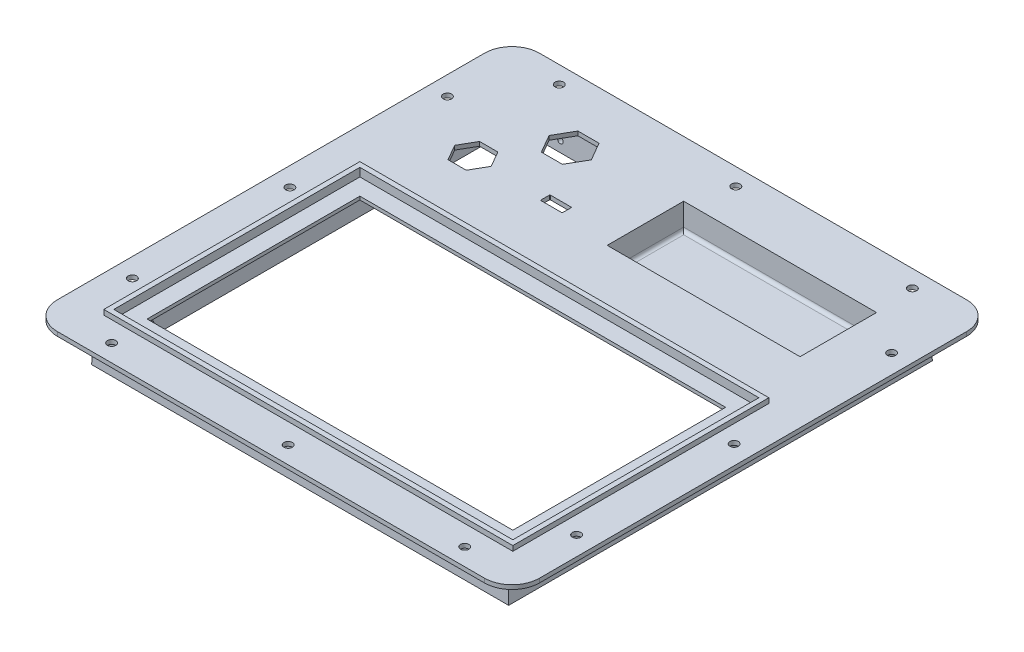
SolidWorks part; units mm, degrees
material "Alumina"
ref_plane "Front Plane" through (0, 0, 0) normal (0, 0, 1) x (1, 0, 0)
ref_plane "Top Plane" through (0, 0, 0) normal (0, 1, 0) x (1, 0, 0)
ref_plane "Right Plane" through (0, 0, 0) normal (1, 0, 0) x (0, 0, -1)
sketch "Sketch1" plane through (0, 0, 0) normal (0, 1, 0) x (1, 0, 0)
  line L1 (-123, -77) -> (123, -77)
  line L2 (-123, -77) -> (-123, 77)
  line L3 (-123, 77) -> (123, 77)
  line L4 (123, -77) -> (123, 77)
  line L5 (-123, -77) -> (123, 77) construction
  line L6 (-123, 77) -> (123, -77) construction
  point P0 (0, 0)
  dimension "D1" = 246
  dimension "D2" = 154
extrude "Boss-Extrude1" add sketch "Sketch1" against normal blind 7
sketch "Sketch2" plane through (0, 0, 0) normal (0, 1, 0) x (1, 0, 0)
  line L1 (-120, -74) -> (120, -74)
  line L2 (-120, -74) -> (-120, 74)
  line L3 (-120, 74) -> (120, 74)
  line L4 (120, -74) -> (120, 74)
  line L5 (-120, -74) -> (120, 74) construction
  line L6 (-120, 74) -> (120, -74) construction
  point P0 (0, 0)
  dimension "D1" = 240
  dimension "D2" = 148
extrude "Cut-Extrude1" cut sketch "Sketch2" against normal blind 5
sketch "Sketch3" plane through (0, -5, 0) normal (0, 1, 0) x (1, 0, 0)
  line L0 (120, 74) -> (-120, 74) construction
  line L1 (-110, -64) -> (110, -64)
  line L2 (-110, -64) -> (-110, 64)
  line L3 (-110, 64) -> (110, 64)
  line L4 (110, -64) -> (110, 64)
  line L5 (-110, -64) -> (110, 64) construction
  line L6 (-110, 64) -> (110, -64) construction
  line L7 (-120, 74) -> (-120, -74) construction
  point P0 (0, 0)
  dimension "D1" = 10
  dimension "D2" = 10
extrude "Cut-Extrude2" cut sketch "Sketch3" against normal blind 5
sketch "Sketch6" plane through (0, 0, 0) normal (0, 1, 0) x (1, 0, 0)
  line L1 (-128.49, -99.5) -> (128.49, -99.5)
  line L5 (-123, -77) -> (123, -77) construction
  line L8 (-145, -82.99) -> (-145, 173.99)
  line L13 (123, -77) -> (123, 77) construction
  line L14 (-123, 77) -> (-123, -77) construction
  line L16 (145, 173.99) -> (145, -82.99)
  line L17 (123, -77) -> (123, 77)
  line L19 (123, 77) -> (-123, 77) construction
  line L20 (-123, -77) -> (123, -77)
  line L21 (-123, 77) -> (-123, -77)
  line L22 (123, 77) -> (-123, 77)
  line L24 (-128.49, 190.5) -> (128.49, 190.5)
  arc A4 (128.49, 190.5) -> (145, 173.99) centre (128.49, 173.99) cw
  arc A5 (-145, 173.99) -> (-128.49, 190.5) centre (-128.49, 173.99) cw
  arc A6 (-128.49, -99.5) -> (-145, -82.99) centre (-128.49, -82.99) cw
  arc A7 (128.49, -99.5) -> (145, -82.99) centre (128.49, -82.99) ccw
  point P0 (0, 0)
  point P2 (0, -99.5)
  point P4 (-146.3741, 193.3595)
  point P9 (-176.0379, 201.6571)
  dimension "D3" = 22
  dimension "D1" = 16.51
  dimension "D10" = 99.5
  dimension "D9" = 16.51
  dimension "D2" = 22.5
  dimension "D6" = 290
  dimension "D12" = 290
extrude "Boss-Extrude2" add sketch "Sketch6" against normal blind 2.5 from offset 3 offset against normal yes
sketch "Sketch8" plane through (0, -5, 0) normal (0, 1, 0) x (1, 0, 0)
  line L0 (-120, -74) -> (120, -74) construction
  line L1 (-19, -73.1) -> (20, -73.1)
  line L2 (-19, -73.1) -> (-19, -72.8)
  line L3 (-19, -72.8) -> (20, -72.8)
  line L4 (20, -73.1) -> (20, -72.8)
  line L5 (-19, -73.1) -> (20, -72.8) construction
  line L6 (-19, -72.8) -> (20, -73.1) construction
  line L8 (-42.26, -73.1) -> (-30, -73.1)
  line L9 (-42.26, -73.1) -> (-42.26, -72.8)
  line L10 (-42.26, -72.8) -> (-30, -72.8)
  line L11 (-30, -73.1) -> (-30, -72.8)
  line L12 (-42.26, -73.1) -> (-30, -72.8) construction
  line L13 (-42.26, -72.8) -> (-30, -73.1) construction
  point P0 (0.5, -72.95)
  point P7 (-36.13, -72.95)
  dimension "D1" = 19
  dimension "D2" = 20
  dimension "D3" = 0.3
  dimension "D4" = 0.9
  dimension "D5" = 12.26
  dimension "D6" = 30
extrude "Cut-Extrude5" cut sketch "Sketch8" against normal blind 5
sketch "Sketch9" plane through (0, -5, 0) normal (0, 1, 0) x (1, 0, 0)
  line L4 (-120, -74) -> (120, -74) construction
  line L5 (120, -74) -> (120, 74) construction
  circle A0 centre (119, -46.2) radius 0.5
  circle A1 centre (119, -42.7) radius 0.5
  dimension "D1" = 1
  dimension "D2" = 1
  dimension "D3" = 27.8
  dimension "D4" = 31.3
extrude "Cut-Extrude6" cut sketch "Sketch9" against normal blind 5
sketch "Sketch10" plane through (0, -3, 0) normal (0, 1, 0) x (1, 0, 0)
  line L0 (0, 157.1305) -> (0, -54.124) construction
  line L1 (-84.5431, 45.5) -> (100.6663, 45.5) construction
  line L2 (145, -82.99) -> (145, 173.99) construction
  circle A0 centre (-133.604, 140.242) radius 2.54
  circle A1 centre (-106.172, 180.12) radius 2.54
  circle A2 centre (-133.604, -49.242) radius 2.54
  circle A3 centre (-133.604, 45.5) radius 2.54
  circle A4 centre (0, 180.12) radius 2.54
  circle A5 centre (0, -89.12) radius 2.54
  circle A6 centre (-106.172, -89.12) radius 2.54
  circle A7 centre (106.172, -89.12) radius 2.54
  circle A8 centre (133.604, 45.5) radius 2.54
  circle A9 centre (133.604, -49.242) radius 2.54
  circle A10 centre (106.172, 180.12) radius 2.54
  circle A11 centre (133.604, 140.242) radius 2.54
  point P29 (145, 45.5)
  dimension "D3" = 5.08
  dimension "D1" = 94.742
  dimension "D2" = 133.604
  dimension "D4" = 134.62
  dimension "D5" = 106.172
  dimension "D6" = 45.5
extrude "Cut-Extrude7" cut sketch "Sketch10" against normal blind 5
sketch "Sketch11" plane through (0, -5.5, 0) normal (0, -1, 0) x (1, 0, 0)
  line L0 (0, 81.15) -> (0, 99.5) construction
  line L1 (-124.65, -172.15) -> (124.65, -172.15)
  line L2 (-124.65, -172.15) -> (-124.65, 81.15)
  line L3 (-124.65, 81.15) -> (124.65, 81.15)
  line L4 (124.65, -172.15) -> (124.65, 81.15)
  line L5 (-124.65, -172.15) -> (124.65, 81.15) construction
  line L6 (-124.65, 81.15) -> (124.65, -172.15) construction
  line L7 (-128.49, 99.5) -> (128.49, 99.5) construction
  line L8 (0, -172.15) -> (0, -190.5) construction
  line L9 (128.49, -190.5) -> (-128.49, -190.5) construction
  line L10 (-122.65, 79.15) -> (122.65, 79.15)
  line L11 (122.65, -170.15) -> (122.65, 79.15)
  line L12 (-122.65, -170.15) -> (122.65, -170.15)
  line L13 (-122.65, -170.15) -> (-122.65, 79.15)
  point P0 (0, -45.5)
  point P10 (0, -142.2375)
  dimension "D1" = 253.3
  dimension "D2" = 249.3
  dimension "D3" = 2
extrude "Boss-Extrude3" add sketch "Sketch11" along normal blind 22 draft 2 draft outward yes
sketch "Sketch12" plane through (124.3063, 4.3409, 0) normal (0.9994, 0.0349, 0) x (0, 0, -1)
  line L0 (45.5, -31.8603) -> (45.5, 60.7594) construction
  line L1 (172.9183, -31.8603) -> (-81.9183, -31.8603) construction
  circle A0 centre (-49.5, -16.8603) radius 1.7
  circle A1 centre (140.5, -16.8603) radius 1.7
  dimension "D1" = 3.4
  dimension "D2" = 15
  dimension "D3" = 95
extrude "Cut-Extrude8" cut sketch "Sketch12" against normal through all
sketch "Sketch13" plane through (0, 2.8237, 80.8593) normal (0, 0.0349, 0.9994) x (1, 0, 0)
  line L0 (0, 0) -> (0, -78.1597) construction
  line L1 (125.4183, -30.3422) -> (-125.4183, -30.3422) construction
  circle A0 centre (-95, -15.3422) radius 1.7
  circle A1 centre (95, -15.3422) radius 1.7
  dimension "D1" = 3.4
  dimension "D2" = 95
  dimension "D3" = 15
extrude "Cut-Extrude9" cut sketch "Sketch13" against normal through all
sketch "Sketch14" plane through (0, -5.5, 0) normal (0, -1, 0) x (1, 0, 0)
  line L0 (123, -77) -> (-123, -77) construction
  line L1 (-10, -108.75) -> (110, -108.75)
  line L2 (-10, -108.75) -> (-10, -158.75)
  line L3 (-10, -158.75) -> (110, -158.75)
  line L4 (110, -108.75) -> (110, -158.75)
  line L5 (-10, -108.75) -> (110, -158.75) construction
  line L6 (-10, -158.75) -> (110, -108.75) construction
  line L8 (123, 77) -> (123, -77) construction
  point P0 (50, -133.75)
  dimension "D1" = 120
  dimension "D2" = 50
  dimension "D3" = 31.75
  dimension "D4" = 13
extrude "Boss-Extrude4" add sketch "Sketch14" along normal blind 15
sketch "Sketch15" plane through (0, -20.5, 0) normal (0, -1, 0) x (1, 0, 0)
  line L0 (108, -110.75) -> (-8, -110.75)
  line L1 (-8, -110.75) -> (-8, -156.75)
  line L2 (-8, -156.75) -> (108, -156.75)
  line L3 (108, -156.75) -> (108, -110.75)
  line L4 (110, -158.75) -> (110, -108.75)
  line L5 (110, -108.75) -> (-10, -108.75)
  line L6 (-10, -108.75) -> (-10, -158.75)
  line L7 (-10, -158.75) -> (110, -158.75)
  line L8 (110, -158.75) -> (110, -108.75) construction
  line L9 (110, -108.75) -> (-10, -108.75) construction
  line L10 (-10, -108.75) -> (-10, -158.75) construction
  line L11 (-10, -158.75) -> (110, -158.75) construction
  dimension "D1" = 0
  dimension "D2" = 2
extrude "Cut-Extrude10" cut sketch "Sketch15" against normal through all from offset 2 offset against normal yes
fillet "Fillet1" radius 2 4 edges at (50, -18.5, -156.75) (-8, -18.5, -133.75) (50, -18.5, -110.75) (108, -18.5, -133.75)
sketch "Sketch16" plane through (0, -3, 0) normal (0, 1, 0) x (1, 0, 0)
  line L0 (128.49, 190.5) -> (-128.49, 190.5) construction
  line L1 (-57.2983, 150.5) -> (-63.6491, 161.5)
  line L2 (-63.6491, 161.5) -> (-76.3509, 161.5)
  line L3 (-76.3509, 161.5) -> (-82.7017, 150.5)
  line L4 (-82.7017, 150.5) -> (-76.3509, 139.5)
  line L5 (-76.3509, 139.5) -> (-63.6491, 139.5)
  line L6 (-63.6491, 139.5) -> (-57.2983, 150.5)
  line L7 (-84.0303, 117) -> (-89.5152, 126.5)
  line L8 (-89.5152, 126.5) -> (-100.4848, 126.5)
  line L9 (-100.4848, 126.5) -> (-105.9697, 117)
  line L10 (-105.9697, 117) -> (-100.4848, 107.5)
  line L11 (-100.4848, 107.5) -> (-89.5152, 107.5)
  line L12 (-89.5152, 107.5) -> (-84.0303, 117)
  line L13 (-51.23, 119.85) -> (-38.77, 119.85)
  line L14 (-51.54, 119.54) -> (-51.54, 114.46)
  line L15 (-51.23, 114.15) -> (-38.77, 114.15)
  line L16 (-38.46, 119.54) -> (-38.46, 114.46)
  line L17 (-51.54, 119.85) -> (-38.46, 114.15) construction
  line L18 (-51.54, 114.15) -> (-38.46, 119.85) construction
  line L19 (123, 77) -> (-123, 77) construction
  line L20 (-145, 173.99) -> (-145, -82.99) construction
  circle A0 centre (-70, 150.5) radius 11 construction
  circle A1 centre (-95, 117) radius 9.5 construction
  arc A2 (-51.23, 114.15) -> (-51.54, 114.46) centre (-51.23, 114.46) cw
  arc A3 (-38.46, 114.46) -> (-38.77, 114.15) centre (-38.77, 114.46) cw
  arc A4 (-38.46, 119.54) -> (-38.77, 119.85) centre (-38.77, 119.54) ccw
  arc A5 (-51.23, 119.85) -> (-51.54, 119.54) centre (-51.23, 119.54) ccw
  point P9 (-45, 117)
  point P27 (0, 0)
  point P28 (0, 0)
  point P29 (-45, 117)
  point P42 (0, 0)
  dimension "D1" = 19
  dimension "D2" = 22
  dimension "D8" = 0.31
  dimension "D9" = 5.08
  dimension "D3" = 40
  dimension "D4" = 40
  dimension "D5" = 25
  dimension "D6" = 25
  dimension "D7" = 50
  dimension "D10" = 12.46
extrude "Cut-Extrude11" cut sketch "Sketch16" against normal through all
